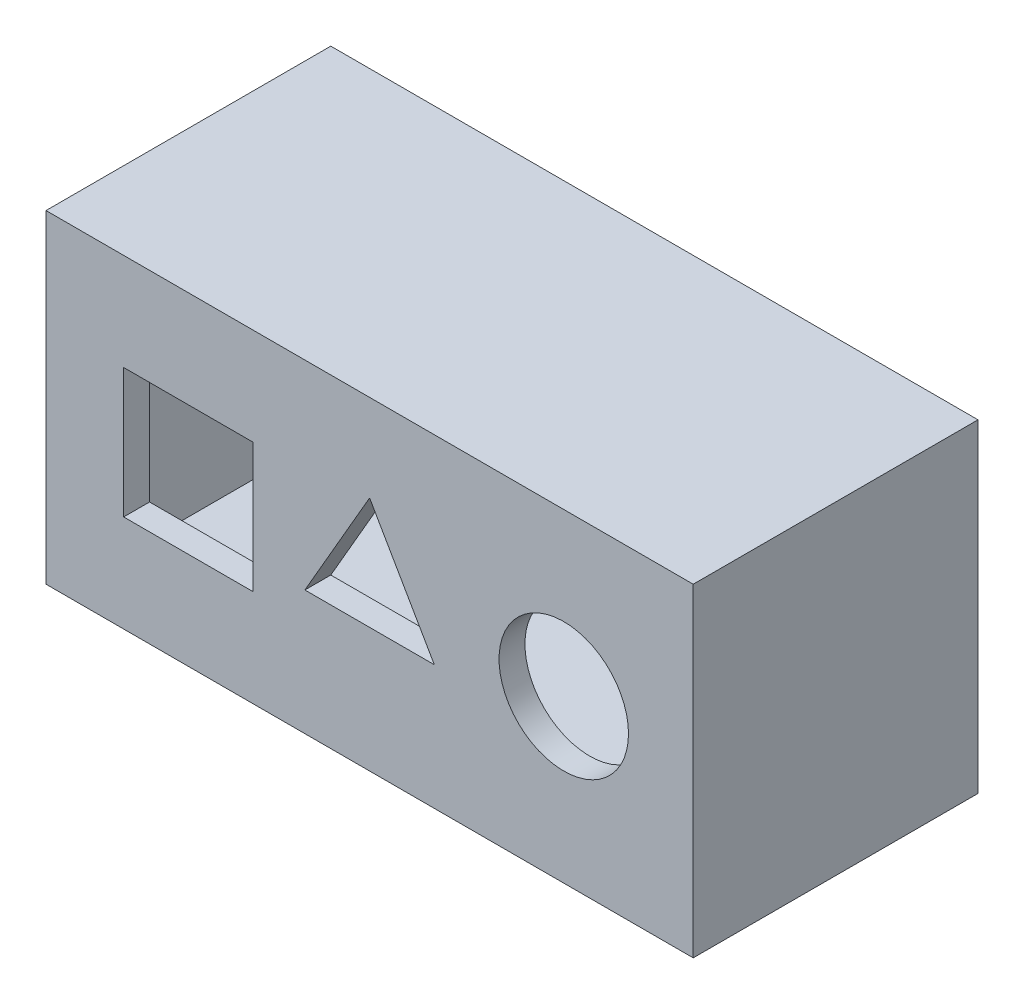
SolidWorks part; units mm, degrees
ref_plane "Front Plane" through (0, 0, 0) normal (0, 0, 1) x (1, 0, 0)
ref_plane "Top Plane" through (0, 0, 0) normal (0, 1, 0) x (1, 0, 0)
ref_plane "Right Plane" through (0, 0, 0) normal (1, 0, 0) x (0, 0, -1)
sketch "Sketch1" plane through (0, 0, 0) normal (0, 0, 1) x (1, 0, 0)
  line L1 (125, -62.5) -> (-125, -62.5)
  line L2 (125, -62.5) -> (125, 62.5)
  line L3 (125, 62.5) -> (-125, 62.5)
  line L4 (-125, -62.5) -> (-125, 62.5)
  line L5 (125, -62.5) -> (-125, 62.5) construction
  line L6 (125, 62.5) -> (-125, -62.5) construction
  line L7 (115, -57.5) -> (-115, -57.5)
  line L8 (115, -57.5) -> (115, 57.5)
  line L9 (115, 57.5) -> (-115, 57.5)
  line L10 (-115, -57.5) -> (-115, 57.5)
  line L11 (115, -57.5) -> (-115, 57.5) construction
  line L12 (115, 57.5) -> (-115, -57.5) construction
  point P0 (0, 0)
  point P6 (0, 0)
  dimension "D1" = 250
  dimension "D2" = 125
  dimension "D3" = 230
extrude "Boss-Extrude1" add sketch "Sketch1" along normal blind 100
sketch "Sketch2" plane through (0, 0, 0) normal (0, 0, -1) x (-1, 0, 0)
  line L1 (125, 62.5) -> (-125, 62.5)
  line L2 (125, 62.5) -> (125, -62.5)
  line L3 (125, -62.5) -> (-125, -62.5)
  line L4 (-125, 62.5) -> (-125, -62.5)
sketch "Sketch3" plane through (0, 0, 100) normal (0, 0, 1) x (1, 0, 0)
  line L0 (-125, 0) -> (125, 0) construction
  line L1 (-125, 62.5) -> (125, 62.5)
  line L2 (-125, 62.5) -> (-125, -62.5)
  line L3 (-125, -62.5) -> (125, -62.5)
  line L4 (125, 62.5) -> (125, -62.5)
  line L5 (0, 62.5) -> (0, -62.5) construction
  line L6 (-25, -14.4338) -> (0, 28.8675)
  line L7 (-95, 25) -> (-45, 25)
  line L8 (-95, 25) -> (-95, -25)
  line L9 (-95, -25) -> (-45, -25)
  line L10 (-45, 25) -> (-45, -25)
  line L11 (-95, 25) -> (-45, -25) construction
  line L12 (-95, -25) -> (-45, 25) construction
  line L14 (-1.3522, 0) -> (0, -1.3522)
  line L18 (0, 28.8675) -> (25, -14.4338)
  line L19 (25, -14.4338) -> (-25, -14.4338)
  line L20 (-25, -14.4338) -> (12.5, 7.2169) construction
  line L21 (25, -14.4338) -> (-12.5, 7.2169) construction
  line L22 (0, 28.8675) -> (0, 0) construction
  circle A0 centre (75, 0) radius 25
  point P10 (-70, 0)
  point P20 (0, 0)
  point P27 (7.7505, -5.3087)
  point P28 (0, 0)
  point P29 (-14.6438, -12.4077)
  point P30 (0, 0)
  point P31 (-22.0562, -11.1232)
  line M21 (-125, 62.5) -> (-125, -62.5)
  line M22 (-125, -62.5) -> (125, -62.5)
  line M23 (125, -62.5) -> (125, 62.5)
  line M24 (125, 62.5) -> (-125, 62.5)
  line M25 (115, -57.5) -> (-115, -57.5)
  line M26 (-115, -57.5) -> (-115, 57.5)
  line M27 (-115, 57.5) -> (115, 57.5)
  line M28 (115, 57.5) -> (115, -57.5)
  dimension "D2" = 50
  dimension "D3" = 50
  dimension "D1" = 30
  dimension "D4" = 50
  dimension "D5" = 50
  dimension "D6" = 50
  dimension "D7" = 50
  dimension "D8" = 50
extrude "Boss-Extrude4" add sketch "Sketch3" along normal blind 10 contours A0 L7 L10 L9 L8 L18 L19 L6 M25 M28 M27 M26 | M24 M21 M22 M23 M28 M25 M26 M27
